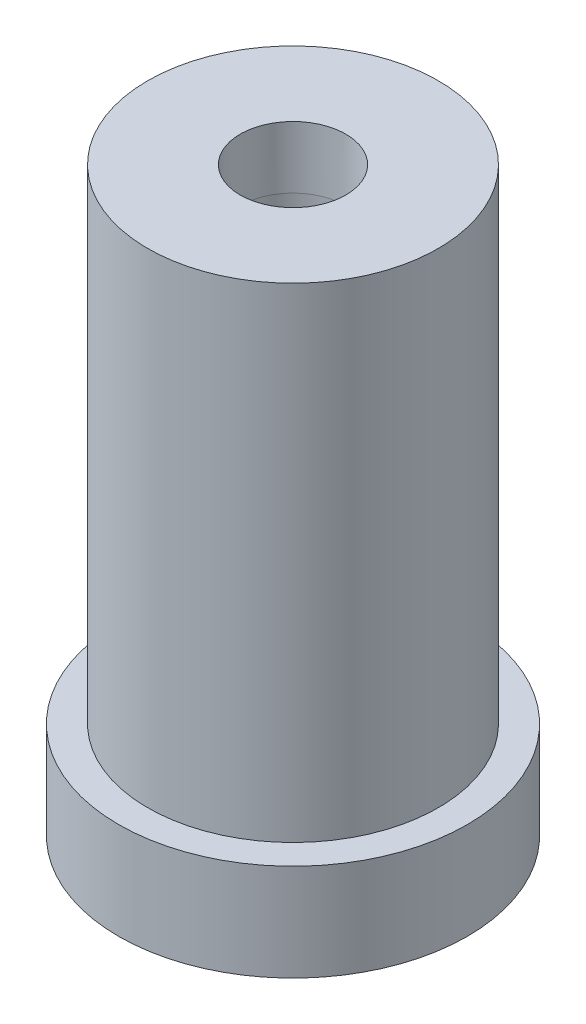
SolidWorks part; units mm, degrees
material "K110"
ref_plane "Front Plane" through (0, 0, 0) normal (0, 0, 1) x (1, 0, 0)
ref_plane "Top Plane" through (0, 0, 0) normal (0, 1, 0) x (1, 0, 0)
ref_plane "Right Plane" through (0, 0, 0) normal (1, 0, 0) x (0, 0, -1)
sketch "Sketch1" plane through (0, 0, 0) normal (0, 0, 1) x (1, 0, 0)
  line L0 (0, 0) -> (9, 0)
  line L1 (9, 0) -> (9, 5)
  line L2 (9, 5) -> (7.5, 5)
  line L3 (7.5, 5) -> (7.5, 30)
  line L4 (7.5, 30) -> (0, 30)
  line L5 (0, 30) -> (0, 0)
  line L6 (0, 35) -> (0, -5) construction
  line L7 (55, 0) -> (-55, 0) construction
  dimension "D1" = 5
  dimension "D2" = 5
  dimension "D3" = 15
  dimension "D4" = 18
  dimension "D5" = 5
  dimension "D6" = 30
revolve "Revolve1" add sketch "Sketch1" angle 360 about L6
sketch "Sketch2" plane through (0, 30, 0) normal (0, 1, 0) x (1, 0, 0)
  circle A0 centre (0, 0) radius 2.725
  dimension "D1" = 5.45
extrude "Cut-Extrude1" cut sketch "Sketch2" against normal up to next
sketch "Sketch3" plane through (0, 0, 0) normal (0, 0, 1) x (1, 0, 0)
  line L0 (2.725, 26.8) -> (3.4268, 0)
  line L1 (2.725, 0) -> (2.725, 30) construction
  line L2 (55, 0) -> (-55, 0) construction
  line L3 (3.4268, 0) -> (2.725, 0)
  line L4 (2.725, 0) -> (2.725, 26.8)
  line L5 (7.5, 30) -> (-7.5, 30) construction
  dimension "D1" = 3.2
  dimension "D2" = 1.5
sweep "Cut-Sweep1" cut profiles "Sketch3" path edge at (0, 30, 2.725)
